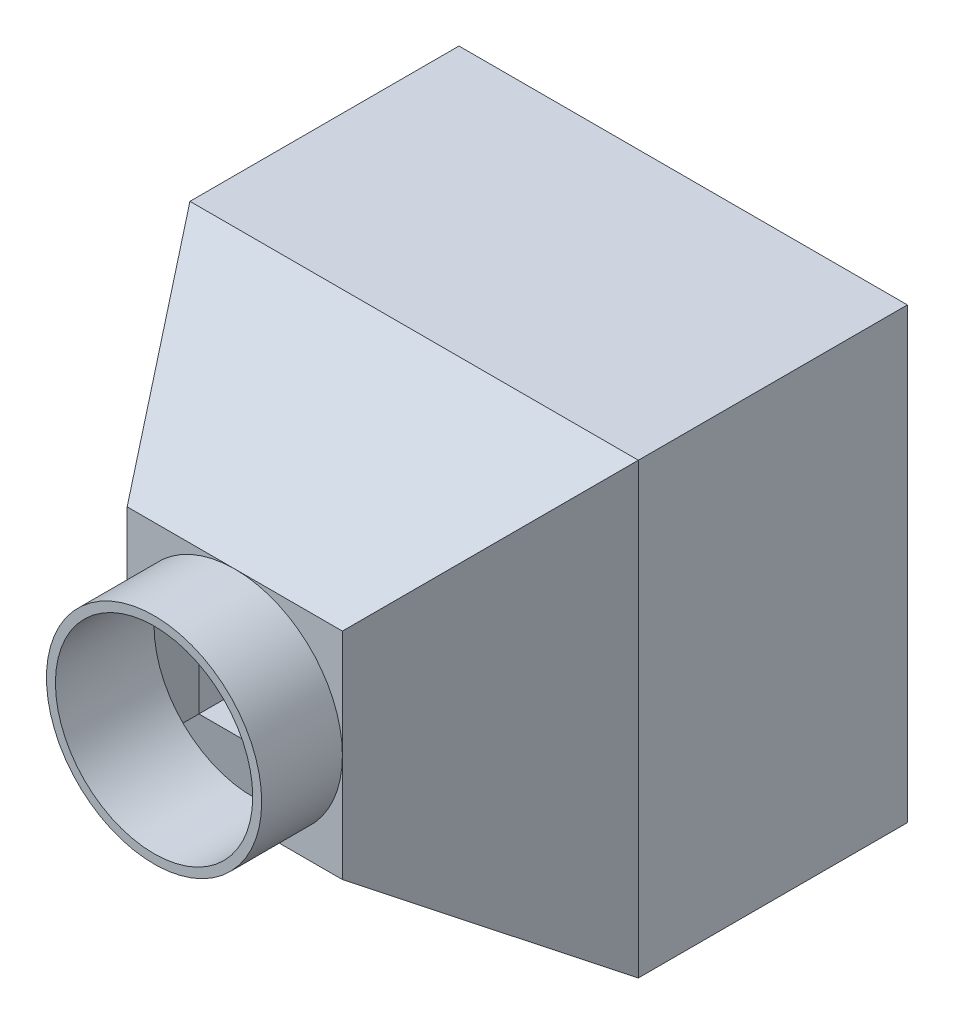
SolidWorks part; units mm, degrees
ref_plane "Спереди" through (0, 0, 0) normal (0, 0, 1) x (1, 0, 0)
ref_plane "Сверху" through (0, 0, 0) normal (0, 1, 0) x (1, 0, 0)
ref_plane "Справа" through (0, 0, 0) normal (1, 0, 0) x (0, 0, -1)
sketch "Эскиз1" plane through (0, 0, 0) normal (0, 0, 1) x (1, 0, 0)
  line L0 (-72.3495, 0) -> (-54.5243, 0) construction
  line L1 (-25, 25) -> (25, 25)
  line L2 (-25, 25) -> (-25, -25)
  line L3 (-25, -25) -> (25, -25)
  line L4 (25, 25) -> (25, -25)
  line L5 (0, 34.5437) -> (0, 23.4757) construction
  dimension "D1" = 50
  dimension "D2" = 50
extrude "Бобышка-Вытянуть1" add sketch "Эскиз1" along normal blind 50
sketch "Эскиз3" plane through (0, 0, 0) normal (0, 0, -1) x (-1, 0, 0)
  line L0 (0, 15.0563) -> (0, -4.9961) construction
  line L1 (-24, 24) -> (24, 24)
  line L2 (-24, 24) -> (-24, -24)
  line L3 (-24, -24) -> (24, -24)
  line L4 (24, 24) -> (24, -24)
  line L5 (-46.2225, 0) -> (47.9219, 0) construction
  dimension "D1" = 48
  dimension "D2" = 48
sketch "Эскиз6" plane through (0, 0, 50) normal (0, 0, 1) x (1, 0, 0)
  circle A0 centre (0, 0) radius 12
  circle A1 centre (0, 0) radius 11
  point P7 (0, 0)
  dimension "D3" = 24
  dimension "D4" = 22
extrude "Бобышка-Вытянуть3" add sketch "Эскиз6" along normal blind 9
sketch "Эскиз17" plane through (0, 0, 50) normal (0, 0, 1) x (1, 0, 0)
  line L1 (-12, -12) -> (12, -12)
  line L2 (-12, -12) -> (-12, 12)
  line L3 (-12, 12) -> (12, 12)
  line L4 (12, -12) -> (12, 12)
  line L5 (-12, -12) -> (12, 12) construction
  line L6 (-12, 12) -> (12, -12) construction
  point P0 (0, 0)
  dimension "D1" = 24
  dimension "D2" = 24
  dimension "D3" = 24
sketch "Эскиз18" plane through (25, 0, 0) normal (1, 0, 0) x (0, 0, -1)
  line L0 (-50, 12) -> (-50, 25)
  line L1 (-50, 25) -> (-30, 25)
  line L2 (-50, 25) -> (0, 25) construction
  line L3 (-30, 25) -> (-50, 12)
  line L4 (-50, -12) -> (-50, -25)
  line L5 (-50, -12) -> (-50, 12) construction
  line L6 (-50, -12) -> (-50, 12) construction
  line L7 (-50, -25) -> (-30, -25)
  line L8 (-50, -25) -> (0, -25) construction
  line L9 (-30, -25) -> (-50, -12)
  dimension "D1" = 20
  dimension "D2" = 13
  dimension "D3" = 23.8537
  dimension "D4" = 13
  dimension "D5" = 20
sketch "Эскиз19" plane through (0, -25, 0) normal (0, -1, 0) x (1, 0, 0)
  line L0 (-12, 50) -> (-25, 50)
  line L1 (-12, 50) -> (12, 50) construction
  line L2 (-25, 50) -> (25, 50) construction
  line L3 (-25, 50) -> (-25, 30)
  line L4 (-25, 50) -> (-25, 0) construction
  line L5 (-25, 30) -> (-12, 50)
  line L6 (12, 50) -> (25, 50)
  line L7 (-12, 50) -> (12, 50) construction
  line L8 (-12, 50) -> (12, 50) construction
  line L9 (25, 50) -> (25, 30)
  line L10 (25, 50) -> (25, 30) construction
  line L11 (25, 30) -> (25, 50) construction
  line L12 (25, 30) -> (12, 50)
  dimension "D1" = 13
  dimension "D2" = 20
  dimension "D3" = 13
  dimension "D4" = 20
extrude "Вырез-Вытянуть5" cut sketch "Эскиз19" against normal up to surface (50 mm away) up to face at (0, 25, 25)
extrude "Вырез-Вытянуть6" cut sketch "Эскиз18" against normal up to surface (50 mm away) up to face at (-25, 0, 15)
sketch "Эскиз20" plane through (0, 0, 0) normal (0, 0, -1) x (-1, 0, 0)
  line L1 (-24, -24) -> (24, -24)
  line L2 (-24, -24) -> (-24, 24)
  line L3 (-24, 24) -> (24, 24)
  line L4 (24, -24) -> (24, 24)
  line L5 (-24, -24) -> (24, 24) construction
  line L6 (-24, 24) -> (24, -24) construction
  point P0 (0, 0)
extrude "Вырез-Вытянуть7" cut sketch "Эскиз20" against normal blind 30
sketch "Эскиз21" plane through (0, 0, 59) normal (0, 0, 1) x (1, 0, 0)
  line L0 (-12, 12) -> (12, -12) construction
  circle A0 centre (0, 0) radius 11
  dimension "D1" = 22
extrude "Вырез-Вытянуть9" cut sketch "Эскиз21" against normal up to surface (29 mm away) up to face at (0, 0, 30)
sketch "Эскиз22" plane through (0, 0, 50) normal (0, 0, 1) x (1, 0, 0)
  line L1 (-11, -11) -> (11, -11)
  line L2 (-11, -11) -> (-11, 11)
  line L3 (-11, 11) -> (11, 11)
  line L4 (11, -11) -> (11, 11)
  line L5 (-11, -11) -> (11, 11) construction
  line L6 (-11, 11) -> (11, -11) construction
  point P0 (0, 0)
  point P5 (0, 0)
  dimension "D1" = 22
  dimension "D2" = 22
sketch "Эскиз28" plane through (0, 0, 30) normal (0, 0, -1) x (-1, 0, 0)
  line L1 (-24, 24) -> (24, 24)
  line L2 (-24, 24) -> (-24, -24)
  line L3 (-24, -24) -> (24, -24)
  line L4 (24, 24) -> (24, -24)
  line L5 (-24, 24) -> (24, -24) construction
  line L6 (-24, -24) -> (24, 24) construction
  point P0 (0, 0)
extrude "Вырез-Вытянуть11" cut sketch "Эскиз28" against normal blind 18 draft 33
